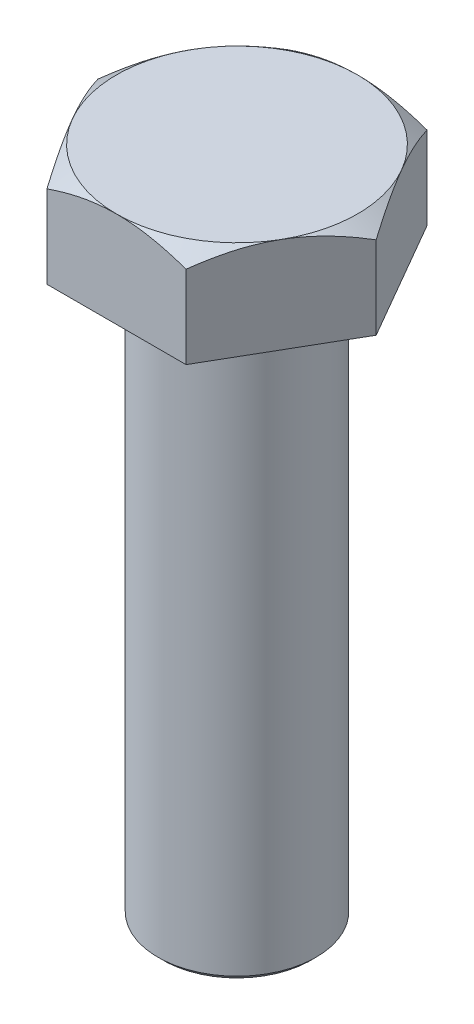
SolidWorks part; units mm, degrees
ref_plane "前视基准面" through (0, 0, 0) normal (0, 0, 1) x (1, 0, 0)
ref_plane "上视基准面" through (0, 0, 0) normal (0, 1, 0) x (1, 0, 0)
ref_plane "右视基准面" through (0, 0, 0) normal (1, 0, 0) x (0, 0, -1)
sketch "草图1" plane through (0, 0, 0) normal (0, 0, 1) x (1, 0, 0)
  line L0 (0, 5.5) -> (8, 5.5)
  line L1 (8, 5.5) -> (8, 0)
  line L2 (8, 0) -> (4.5455, 0)
  line L3 (4.5455, 0) -> (4.5455, -33)
  line L4 (4.5455, -33) -> (0, -33)
  line L5 (0, 0) -> (0, 5.5) construction
  line L6 (0, -33) -> (0, 5.5)
  point P6 (5, 0)
  point P9 (0, -26)
  point P10 (8, 2.75)
  dimension "D1" = 9.0909
  dimension "D" = 10
  dimension "D2" = 16
  dimension "L" = 26
  dimension "D3" = 5.5
  dimension "D4" = 7
revolve "旋转1" add sketch "草图1" angle 360 about L5
sketch "草图2" plane through (0, 0, 0) normal (0, 1, 0) x (1, 0, 0)
  line L1 (8, 0) -> (4, 6.9282)
  line L2 (4, 6.9282) -> (-4, 6.9282)
  line L3 (-4, 6.9282) -> (-8, 0)
  line L4 (-8, 0) -> (-4, -6.9282)
  line L5 (-4, -6.9282) -> (4, -6.9282)
  line L6 (4, -6.9282) -> (8, 0)
  circle A0 centre (0, 0) radius 6.9282 construction
extrude "切除-拉伸1" cut sketch "草图2" along normal up to vertex (5.5 mm away) flip side to cut up to point (8, 5.5, 0)
sketch "草图3" plane through (0, 0, 0) normal (0, 1, 0) x (1, 0, 0)
  circle A0 centre (0, 0) radius 6.9282 construction
  circle A1 centre (0, 0) radius 6.9282
extrude "切除-拉伸2" cut sketch "草图3" against normal up to vertex (-2.75 mm away) draft 55 from vertex at 5.5 flip side to cut starting at point (8, 5.5, 0)
chamfer "倒角1" distance 0.3 angle 45 1 edges at (0, -33, -4.5455)
equation "\"D1@草图1\" = \"D@草图1\"/1.1"
equation "\"D2@草图1\" = \"D@草图1\"*1.6"
equation "\"D3@草图1\" = \"D@草图1\"*0.55"
equation "\"D4@草图1\" = \"D@草图1\"*0.7"
equation "\"D1@倒角1\" = \"D@草图1\"/100+0.2"
